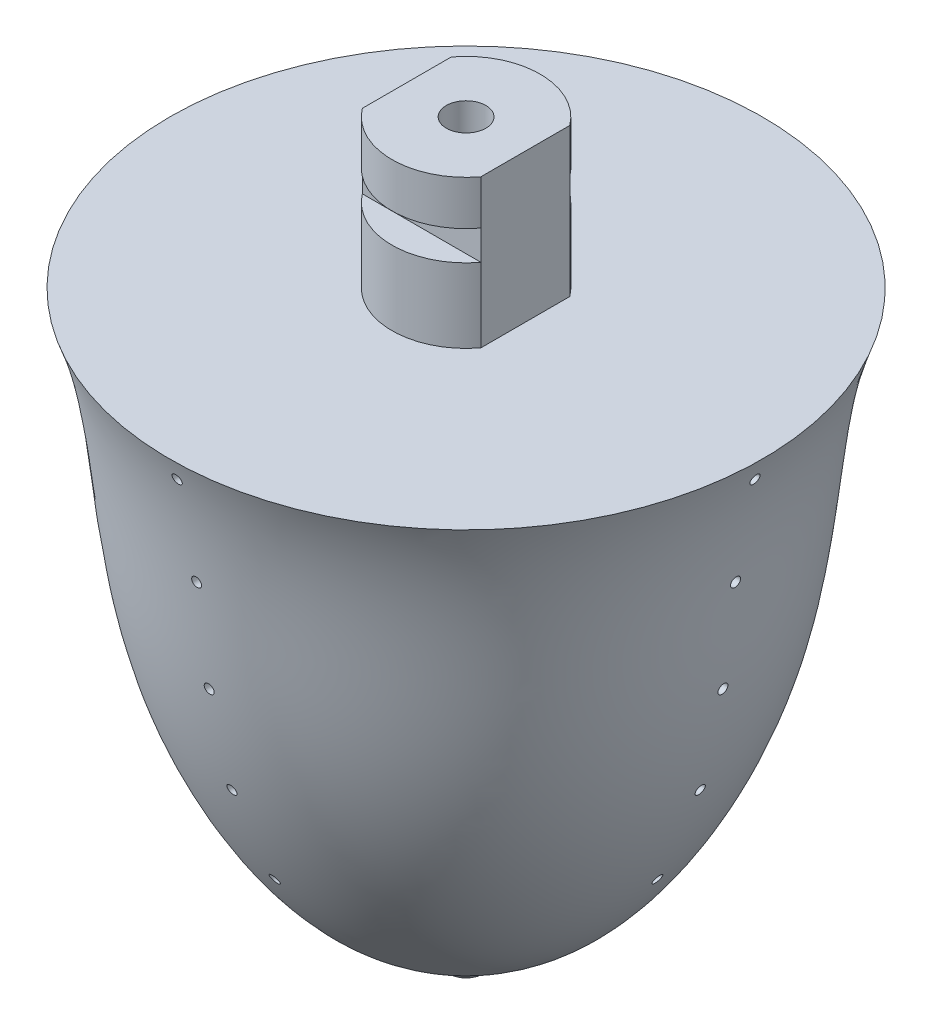
SolidWorks part; units mm, degrees
material "ABS"
ref_plane "Front" through (0, 0, 0) normal (0, 0, 1) x (1, 0, 0)
ref_plane "Top" through (0, 0, 0) normal (0, 1, 0) x (1, 0, 0)
ref_plane "Right" through (0, 0, 0) normal (1, 0, 0) x (0, 0, -1)
sketch "Sketch1" plane through (0, 0, 0) normal (0, 0, 1) x (1, 0, 0)
  line L0 (0, 0) -> (0, -120) construction
  line L5 (0, 0) -> (60, 0)
  line L7 (0, 0) -> (0, -120)
  arc A2 (13.0773, -110) -> (5.3316, -116.4065) centre (17.7581, -123.545) ccw
  arc A3 (5.3316, -116.4065) -> (0, -120) centre (-0.9946, -112.7725) cw
  spline S0 degree 3 poles (13.0773, -110) (26.4415, -105.3816) (58.4, -57.5711) (51.5987, -21.7946) (60, 0) knots 0.017668 0.017668 0.017668 0.017668 0.353401 1 1 1 1
  dimension "D2" = 110
  dimension "D1" = 120
  dimension "D3" = 60
revolve "Revolve5" add sketch "Sketch1" angle 360 about L0
sketch "Sketch2" plane through (0, 0, 0) normal (0, 1, 0) x (1, 0, 0)
  line L0 (60, 0) -> (-60, 0) construction
  line L1 (12, 9) -> (12, -9)
  line L2 (-12, 9) -> (-12, -9)
  line L3 (12, -9) -> (-12, -9) construction
  line L4 (-12, 9) -> (12, 9) construction
  arc A0 (-12, -9) -> (12, -9) centre (0, 0) ccw
  circle A1 centre (0, 0) radius 60 construction
  arc A4 (12, 9) -> (-12, 9) centre (0, 0) ccw
  dimension "D1" = 30
  dimension "D2" = 12
  dimension "D3" = 12
extrude "Boss-Extrude1" add sketch "Sketch2" along normal blind 30
sketch "Sketch3" plane through (0, 30, 0) normal (0, 1, 0) x (1, 0, 0)
  circle A0 centre (0, 0) radius 4
  dimension "D1" = 8
extrude "Cut-Extrude1" cut sketch "Sketch3" against normal blind 30
ref_plane "Plane1" through (0, 0, 9) normal (0, 0, 1) x (1, 0, 0)
sketch "Sketch5" plane through (0, 0, 9) normal (0, 0, 1) x (1, 0, 0)
  line L0 (-12, 30) -> (-12, 0) construction
  line L1 (-12, 21) -> (12, 21)
  line L2 (-12, 21) -> (-12, 15)
  line L3 (-12, 15) -> (12, 15)
  line L4 (12, 21) -> (12, 15)
  line L5 (12, 30) -> (12, 0) construction
  dimension "D1" = 6
extrude "Cut-Extrude2" cut sketch "Sketch5" along normal up to next
mirror "Mirror1" about plane through (0, 0, 0) normal (0, 0, 1) of "Cut-Extrude2"
sketch "Sketch6" plane through (0, 0, 0) normal (1, 0, 0) x (0, 0, -1)
  line L0 (0, 0) -> (0, -120) construction
  line L1 (0, -40.4475) -> (0, 80.895) construction
  circle A0 centre (0, -4.2983) radius 1
  circle A1 centre (0, -24.2983) radius 1
  circle A2 centre (0, -44.2983) radius 1
  circle A3 centre (0, -84.2983) radius 1
  circle A4 centre (0, -104.2983) radius 1
  circle A5 centre (0, -64.2983) radius 1
  point P14 (0, -12.476)
  point P17 (0, -23.6622)
  point P18 (0, -39.9007)
  point P21 (0, -58.7254)
  point P22 (0, -104.2983)
  point P23 (0, -84.0675)
  dimension "D6" = 2
  dimension "D1" = 20
  dimension "D2" = 20
  dimension "D3" = 20
  dimension "D4" = 20
  dimension "D5" = 20
extrude "Cut-Extrude3" cut sketch "Sketch6" against normal up to next
pattern_circular "CirPattern1" count 4 every 90 about axis through (0, 0, 0) along (0, 1, 0) of "Cut-Extrude3"
